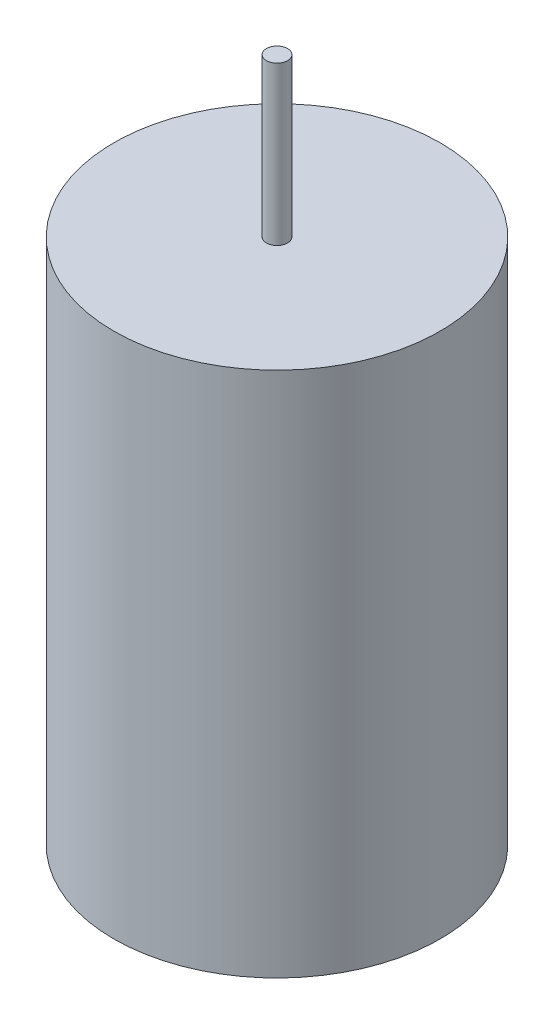
SolidWorks part; units mm, degrees
ref_plane "Front Plane" through (0, 0, 0) normal (0, 0, 1) x (1, 0, 0)
ref_plane "Top Plane" through (0, 0, 0) normal (0, 1, 0) x (1, 0, 0)
ref_plane "Right Plane" through (0, 0, 0) normal (1, 0, 0) x (0, 0, -1)
sketch "Sketch1" plane through (0, 0, 0) normal (0, 1, 0) x (1, 0, 0)
  circle A0 centre (0, 0) radius 15.5
  dimension "D1" = 31
extrude "Boss-Extrude1" add sketch "Sketch1" along normal blind 50
sketch "Sketch2" plane through (0, 50, 0) normal (0, 1, 0) x (1, 0, 0)
  circle A0 centre (0, 0) radius 1
  dimension "D1" = 2
extrude "Boss-Extrude2" add sketch "Sketch2" along normal blind 15
